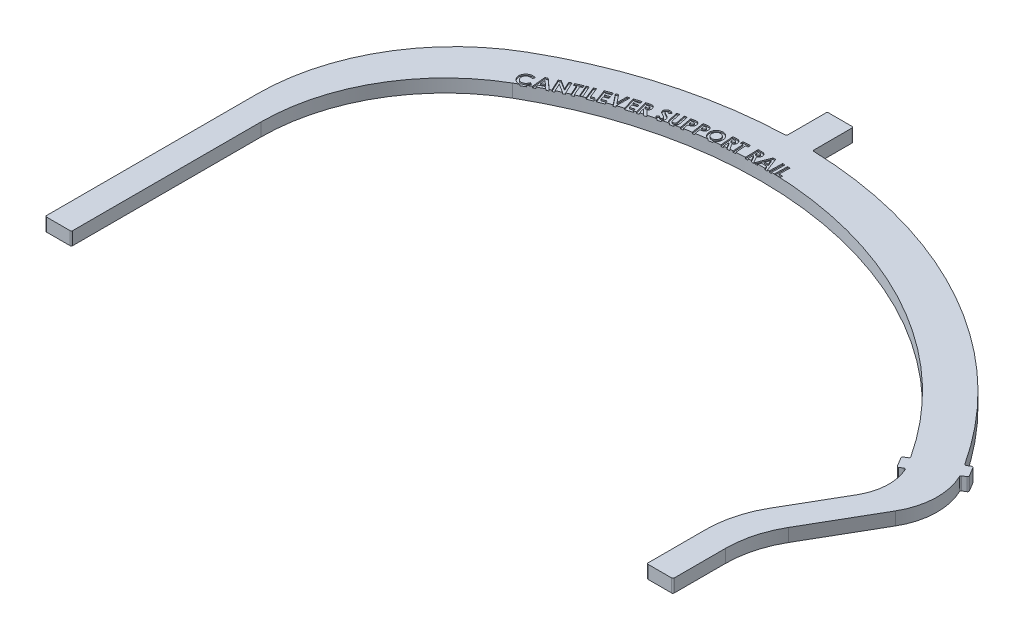
SolidWorks part; units mm, degrees
ref_plane "Front Plane" through (0, 0, 0) normal (0, 0, 1) x (1, 0, 0)
ref_plane "Top Plane" through (0, 0, 0) normal (0, 1, 0) x (1, 0, 0)
ref_plane "Right Plane" through (0, 0, 0) normal (1, 0, 0) x (0, 0, -1)
sketch "Sketch1" plane through (0, 0, 0) normal (0, 1, 0) x (1, 0, 0)
  line L0 (-289.6944, 501.7654) -> (0, 0) construction
  line L1 (0, 0) -> (491.5781, 307.1721) construction
  line L2 (-109.0546, 383.5787) -> (-103.845, 365.2548) construction
  line L4 (12.7, 417.6369) -> (12.7, 457.2)
  line L5 (12.7, 457.2) -> (-12.7, 457.2)
  line L6 (-12.7, 417.6369) -> (-12.7, 457.2)
  line L8 (-279.4, 173.7767) -> (-279.4, -10.16)
  line L9 (-279.4, -10.16) -> (-304.8, -10.16)
  line L10 (-304.8, 195.7737) -> (-304.8, -10.16)
  line L12 (279.4, 47.214) -> (279.4, -10.16)
  line L13 (279.4, -10.16) -> (304.8, -10.16)
  line L14 (304.8, 40.64) -> (304.8, -10.16)
  line L15 (-109.0546, 383.5787) -> (-114.2642, 401.9025) construction
  line L16 (-264.8195, 339.2934) -> (17.9737, 419.6938) construction
  line L17 (0, 0) -> (0, 457.2) construction
  line L19 (323.6431, 149.9978) -> (292.4763, 96.0153)
  line L21 (317.7603, 89.0086) -> (355.8603, 154.9997)
  line L22 (321.8984, 201.1445) -> (354.2132, 221.337) construction
  line L25 (318.6197, 206.5825) -> (325.1772, 195.7064) construction
  line L26 (318.6197, 206.5825) -> (313.1817, 203.3038)
  line L27 (357.4919, 215.8989) -> (350.9345, 226.775) construction
  line L28 (313.1817, 203.3038) -> (319.7391, 192.4277)
  line L29 (319.7391, 192.4277) -> (325.1772, 195.7064)
  line L30 (357.4919, 215.8989) -> (362.93, 219.1776)
  line L31 (362.93, 219.1776) -> (356.3725, 230.0537)
  line L32 (356.3725, 230.0537) -> (350.9345, 226.775)
  arc A0 (-189.865, 328.8558) -> (318.6197, 206.5825) centre (0, 0) cw
  arc A1 (-208.915, 361.8514) -> (-12.7, 417.6369) centre (0, 0) cw
  arc A3 (-189.865, 328.8558) -> (-279.4, 173.7767) centre (-100.33, 173.7767) ccw
  arc A4 (-208.915, 361.8514) -> (-304.8, 195.7737) centre (-113.03, 195.7737) ccw
  arc A5 (325.1772, 195.7064) -> (323.6431, 149.9978) centre (281.5677, 174.29) cw
  arc A6 (357.4919, 215.8989) -> (355.8603, 154.9997) centre (300.5139, 186.954) cw
  arc A7 (-199.39, 345.3536) -> (338.1846, 211.3212) centre (0, 0) cw construction
  arc A8 (12.7, 417.6369) -> (350.9345, 226.775) centre (0, 0) cw
  arc A12 (292.4763, 96.0153) -> (279.4, 47.214) centre (377.0026, 47.214) ccw
  arc A13 (317.7603, 89.0086) -> (304.8, 40.64) centre (401.5371, 40.64) ccw
  dimension "D1" = 398.78
  dimension "D2" = 19.05
  dimension "D16" = 25.4
  dimension "D17" = 12.7
  dimension "D3" = 30
  dimension "D4" = 58
  dimension "D5" = 279.4
  dimension "D6" = 279.4
  dimension "D7" = 25.4
  dimension "D8" = 25.4
  dimension "D9" = 25.4
  dimension "D10" = 10.16
  dimension "D11" = 457.2
  dimension "D12" = 25.4
  dimension "D13" = 150
  dimension "D14" = 76.2
  dimension "D15" = 50.8
  dimension "D18" = 38.1
  dimension "D19" = 6.35
extrude "Boss-Extrude1" add sketch "Sketch1" along normal blind 12.7
fillet "Fillet1" radius 1.27 16 edges at (12.7, 6.35, -417.6369) (-12.7, 6.35, -417.6369) (318.6197, 6.35, -206.5825) (350.9345, 6.35, -226.775) (357.4919, 6.35, -215.8989) (325.1772, 6.35, -195.7064) (356.3725, 6.35, -230.0537) (362.93, 6.35, -219.1776) (313.1817, 6.35, -203.3038) (319.7391, 6.35, -192.4277) (279.4, 6.35, 10.16) (304.8, 6.35, 10.16) (-304.8, 6.35, 10.16) (-279.4, 6.35, 10.16) (-12.7, 6.35, -457.2) (12.7, 6.35, -457.2)
sketch "Sketch2" plane through (0, 12.7, 0) normal (0, 1, 0) x (1, 0, 0)
  text T0 "<b>CANTILEVER SUPPORT RAIL</b>" font "Century Gothic" height 12.7
extrude "Cut-Extrude1" cut sketch "Sketch2" against normal blind 1.27
sketch "Sketch3" plane through (0, 12.7, 0) normal (0, 1, 0) x (1, 0, 0)
  line L0 (-303.53, -10.16) -> (-280.67, -10.16) construction
  line L1 (-330.2, 358.14) -> (-190.5, 358.14) construction
  line L2 (-330.2, 358.14) -> (-330.2, -35.56) construction
  line L3 (-330.2, -35.56) -> (-190.5, -35.56) construction
  line L4 (-190.5, 358.14) -> (-190.5, -35.56) construction
  line L5 (-304.8, 195.7737) -> (-304.8, -8.89) construction
  line L6 (11.43, 457.2) -> (-11.43, 457.2) construction
  line L7 (-228.6, 469.9) -> (228.6, 469.9) construction
  line L8 (-228.6, 469.9) -> (-228.6, 317.5) construction
  line L9 (-228.6, 317.5) -> (228.6, 317.5) construction
  line L10 (228.6, 469.9) -> (228.6, 317.5) construction
  line L11 (-220.8717, 354.3483) -> (-213.7298, 343.8467)
  line L12 (177.8, 368.3) -> (482.6, 368.3) construction
  line L13 (177.8, 368.3) -> (177.8, -215.9) construction
  line L14 (177.8, -215.9) -> (482.6, -215.9) construction
  line L15 (482.6, 368.3) -> (482.6, -215.9) construction
  line L16 (-213.7298, 343.8467) -> (-203.2282, 350.9885)
  line L17 (-203.2282, 350.9885) -> (-196.0864, 340.4869)
  line L18 (-196.0864, 340.4869) -> (-206.588, 333.3451)
  line L19 (-206.588, 333.3451) -> (-199.4794, 322.8923)
  line L20 (-199.4794, 322.8923) -> (193.8267, 326.5365)
  line L21 (193.8267, 326.5365) -> (200.5026, 337.3403)
  line L22 (200.5026, 337.3403) -> (211.3064, 330.6644)
  line L23 (211.3064, 330.6644) -> (217.0977, 340.0365)
  line L24 (217.0977, 340.0365) -> (206.2939, 346.7125)
  line L25 (206.2939, 346.7125) -> (213.8574, 358.9525)
  line L26 (-220.8717, 354.3483) -> (-14.5106, 556.3651)
  line L27 (-14.5106, 556.3651) -> (213.8574, 358.9525)
  line L28 (-14.5106, 556.3651) -> (-467.7636, 531.2601)
  line L29 (-467.7636, 531.2601) -> (-348.2805, -153.4703)
  line L30 (-348.2805, -153.4703) -> (535.5885, -124.3655)
  line L31 (535.5885, -124.3655) -> (416.8033, 556.3651)
  line L32 (416.8033, 556.3651) -> (-14.5106, 556.3651)
  line L33 (-2.8263, 324.7144) -> (59.1877, -138.9179)
  line L34 (59.1877, -138.9179) -> (0, -196.8596)
  arc A0 (-208.915, 361.8514) -> (-304.8, 195.7737) centre (-113.03, 195.7737) ccw construction
  arc A1 (-189.865, 328.8558) -> (-279.4, 173.7767) centre (-100.33, 173.7767) ccw construction
  arc A2 (-185.4337, 331.3748) -> (-189.865, 328.8558) centre (0, 0) ccw construction
  arc A3 (350.2668, 227.8049) -> (13.9277, 417.5978) centre (0, 0) ccw construction
  dimension "D1" = 139.7
  dimension "D2" = 393.7
  dimension "D3" = 25.4
  dimension "D4" = 25.4
  dimension "D5" = 152.4
  dimension "D6" = 457.2
  dimension "D7" = 12.7
  dimension "D8" = 38.1
  dimension "D9" = 304.8
  dimension "D10" = 584.2
  dimension "D11" = 50.8
  dimension "D12" = 50.8
  dimension "D13" = 12.7
  dimension "D14" = 12.7
  dimension "D15" = 12.7
  dimension "D16" = 12.7
  dimension "D17" = 12.7
